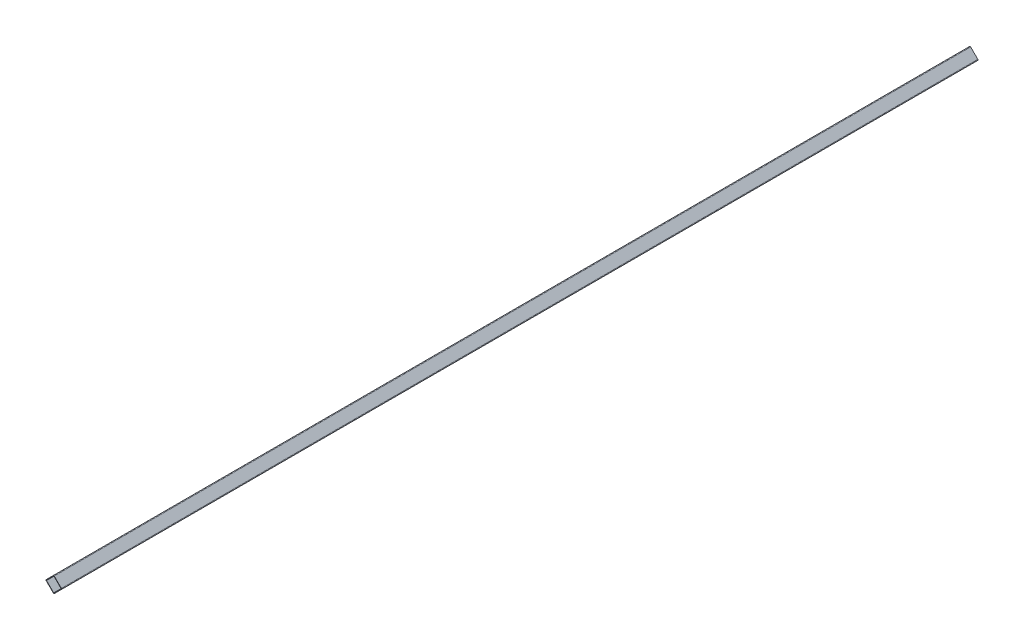
SolidWorks part; units mm, degrees
ref_plane "Front" through (0, 0, 0) normal (0, 0, 1) x (1, 0, 0)
ref_plane "Top" through (0, 0, 0) normal (0, 1, 0) x (1, 0, 0)
ref_plane "Right" through (0, 0, 0) normal (1, 0, 0) x (0, 0, -1)
sketch "inch square tube" plane through (0, 0, 0) normal (0, 0, 1) x (1, 0, 0)
  line L0 (0, 0) -> (-13.4704, -13.4704) construction
  line L1 (25.2437, -1.6971) -> (1.6971, -25.2437)
  line L2 (25.2437, 1.6971) -> (1.6971, 25.2437)
  line L3 (-1.6971, 25.2437) -> (-25.2437, 1.6971)
  line L4 (-1.6971, -25.2437) -> (-25.2437, -1.6971)
  line L5 (0, 0) -> (13.4704, -13.4704) construction
  line L7 (-24.1123, 0.5657) -> (-0.5657, 24.1123)
  line L8 (-24.1123, -0.5657) -> (-0.5657, -24.1123)
  line L9 (0.5657, -24.1123) -> (24.1123, -0.5657)
  line L10 (0.5657, 24.1123) -> (24.1123, 0.5657)
  circle A0 centre (0, 0) radius 14.1224 construction
  arc A1 (1.6971, -25.2437) -> (-1.6971, -25.2437) centre (0, -23.5467) cw
  arc A2 (25.2437, -1.6971) -> (25.2437, 1.6971) centre (23.5467, 0) ccw
  arc A3 (1.6971, 25.2437) -> (-1.6971, 25.2437) centre (0, 23.5467) ccw
  arc A4 (-25.2437, 1.6971) -> (-25.2437, -1.6971) centre (-23.5467, 0) ccw
  arc A5 (-0.5657, 24.1123) -> (0.5657, 24.1123) centre (0, 23.5467) cw
  arc A6 (24.1123, -0.5657) -> (24.1123, 0.5657) centre (23.5467, 0) ccw
  arc A7 (-0.5657, -24.1123) -> (0.5657, -24.1123) centre (0, -23.5467) ccw
  arc A8 (-24.1123, 0.5657) -> (-24.1123, -0.5657) centre (-23.5467, 0) ccw
  point P0 (0, 0)
  point P1 (-12.339, -12.339)
  point P4 (12.339, -12.339)
  point P12 (13.4704, 13.4704)
  point P13 (-13.4704, -13.4704)
  point P14 (-13.4704, 13.4704)
  point P35 (0, -26.9408)
  point P36 (13.4704, -13.4704)
  point P37 (-26.9408, 0)
  point P38 (0, 26.9408)
  point P39 (26.9408, 0)
  point P41 (0, 0)
  point P42 (0, 0)
  dimension "D2" = 14.1224
  dimension "D4" = 2.4
  dimension "D5" = 0.8
  dimension "D3" = 1.6
  dimension "D1" = 38.1
extrude "Boss-Extrude1" add sketch "inch square tube" along normal blind 3048
equation "\"D4@inch square tube\" = \"D3@inch square tube\" * 1.5"
equation "\"D5@inch square tube\" = \"D4@inch square tube\" - \"D3@inch square tube\""
equation "\"10feet\"=0.6"
